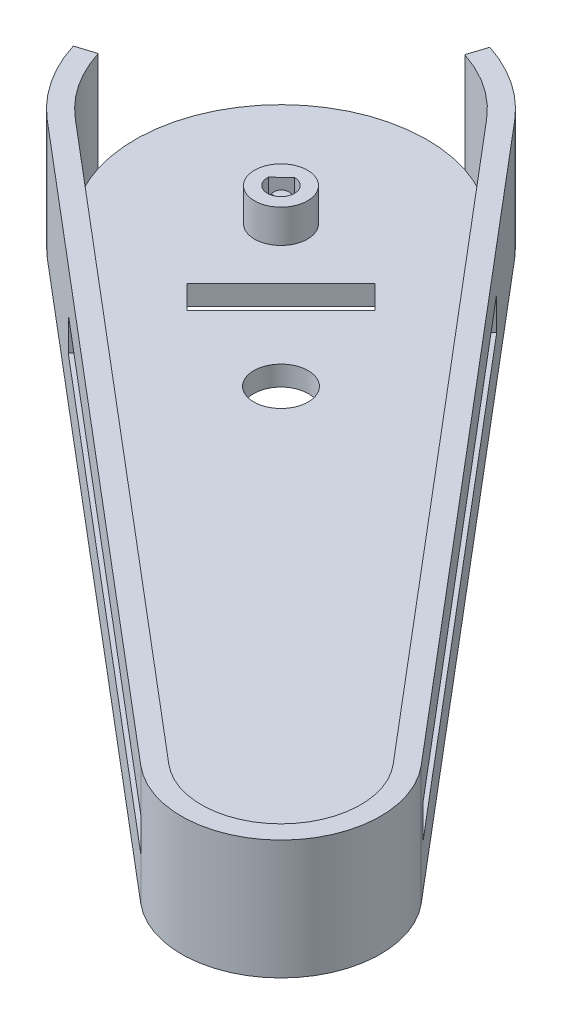
SolidWorks part; units mm, degrees
ref_plane "前视基准面" through (0, 0, 0) normal (0, 0, 1) x (1, 0, 0)
ref_plane "上视基准面" through (0, 0, 0) normal (0, 1, 0) x (1, 0, 0)
ref_plane "右视基准面" through (0, 0, 0) normal (1, 0, 0) x (0, 0, -1)
other "Configuration Table"
sketch "草图2" plane through (0, 0, 0) normal (0, 1, 0) x (1, 0, 0)
  line L0 (-140.5033, 0) -> (6884.6605, 0) construction
  line L1 (0, -140.5033) -> (0, 6884.6605) construction
  line L2 (0, 0) -> (42.4264, -42.4264)
  line L3 (42.4264, -42.4264) -> (-42.4264, 42.4264)
  line L4 (-58.5694, 23.3371) -> (32.7406, -53.88)
  line L5 (-23.3371, 58.5694) -> (53.88, -32.7406)
  circle A0 centre (-42.4264, 42.4264) radius 25
  circle A1 centre (42.4264, -42.4264) radius 15
  dimension "D3" = 50
  dimension "D4" = 30
  dimension "D1" = 60
  dimension "D2" = 120
extrude "凸台-拉伸2" add sketch "草图2" along normal blind 3
sketch "草图4" plane through (0, 3, 0) normal (0, 1, 0) x (1, 0, 0)
  line L0 (-58.5694, 23.3371) -> (32.7406, -53.88)
  line L1 (-58.5694, 23.3371) -> (32.7406, -53.88) construction
  line L2 (-23.3371, 58.5694) -> (53.88, -32.7406)
  line L3 (-23.3371, 58.5694) -> (53.88, -32.7406) construction
  line L4 (-56.6323, 25.6278) -> (34.6777, -51.5893)
  line L5 (-25.6278, 56.6323) -> (51.5893, -34.6777)
  circle A0 centre (-42.4264, 42.4264) radius 25
  circle A1 centre (42.4264, -42.4264) radius 15
  circle A2 centre (-42.4264, 42.4264) radius 22
  circle A3 centre (42.4264, -42.4264) radius 12
  circle A4 centre (-42.4264, 42.4264) radius 2.25
  circle A5 centre (42.4264, -42.4264) radius 2.5
  dimension "D3" = 4.5
  dimension "D4" = 5
  dimension "D1" = 3
  dimension "D2" = 3
extrude "切除-拉伸2" cut sketch "草图4" against normal through all contours A4 | A5
sketch "草图6" plane through (0, 3, 0) normal (0, 1, 0) x (1, 0, 0)
  circle A0 centre (-42.4264, 42.4264) radius 3.5
  dimension "D1" = 7
extrude "切除-拉伸3" cut sketch "草图6" against normal through all
sketch "草图7" plane through (0, 3, 0) normal (0, 1, 0) x (1, 0, 0)
  circle A0 centre (42.4264, -42.4264) radius 3.5
  dimension "D1" = 7
extrude "切除-拉伸4" cut sketch "草图7" against normal through all
sketch "草图8" plane through (0, 3, 0) normal (0, 1, 0) x (1, 0, 0)
  line L0 (-11.8521, 30.3069) -> (-26.8914, 12.9805)
  line L1 (-26.8914, 12.9805) -> (25.2188, -32.2512)
  line L2 (25.2188, -32.2512) -> (33.6267, -22.5647)
  line L3 (33.6267, -22.5647) -> (-15.703, 25.8704)
extrude "切除-拉伸5" cut sketch "草图8" against normal through all contours L2 L3 L0 L1
sketch "草图9" plane through (0, 3, 0) normal (0, 1, 0) x (1, 0, 0)
  line L0 (-23.3371, 58.5694) -> (53.88, -32.7406)
  line L1 (-58.5694, 23.3371) -> (32.7406, -53.88)
  line L2 (-56.6323, 25.6278) -> (34.6777, -51.5893)
  line L3 (-25.6278, 56.6323) -> (51.5893, -34.6777)
  circle A0 centre (-42.4264, 42.4264) radius 25
  circle A1 centre (42.4264, -42.4264) radius 15
  circle A2 centre (-42.4264, 42.4264) radius 22
  circle A3 centre (42.4264, -42.4264) radius 12
  line M8 (-58.5694, 23.3371) -> (32.7406, -53.88)
  arc M9 (32.7406, -53.88) -> (53.88, -32.7406) centre (42.4264, -42.4264) ccw
  line M10 (53.88, -32.7406) -> (-23.3371, 58.5694)
  arc M11 (-23.3371, 58.5694) -> (-58.5694, 23.3371) centre (-42.4264, 42.4264) ccw
  dimension "D1" = 3
  dimension "D2" = 3
extrude "凸台-拉伸4" add sketch "草图9" along normal blind 15 contours A2 L3 A0 L2 M11 | A1 A0 L3 M10 | A1 L2 A0 M8 | A3 L2 A1 L3 M9
sketch "草图10" plane through (0, 3, 0) normal (0, 1, 0) x (1, 0, 0)
  line L0 (-42.4264, 42.4264) -> (42.4264, -42.4264)
  line L1 (42.4264, -42.4264) -> (10.5288, -10.5288)
  line L2 (-26.8914, 12.9805) -> (-15.703, 25.8704)
  line L3 (-15.703, 25.8704) -> (33.6267, -22.5647)
  line L4 (33.6267, -22.5647) -> (25.2188, -32.2512)
  line L5 (25.2188, -32.2512) -> (-26.8914, 12.9805)
  line M5 (33.6267, -22.5647) -> (25.2188, -32.2512)
  line M6 (25.2188, -32.2512) -> (-26.8914, 12.9805)
  line M7 (-26.8914, 12.9805) -> (-15.703, 25.8704)
  line M8 (-15.703, 25.8704) -> (33.6267, -22.5647)
extrude "凸台-拉伸5" add sketch "草图10" against normal blind 3 contours L0 M7 M6 M5 | L0 M7 M5 M8
sketch "草图11" plane through (0, 3, 0) normal (0, 1, 0) x (1, 0, 0)
  line L0 (-42.4264, 42.4264) -> (42.4264, -42.4264)
  line L1 (42.4264, -42.4264) -> (-21.2132, 21.2132)
  circle A0 centre (-21.2132, 21.2132) radius 4.1
  circle A2 centre (42.4264, -42.4264) radius 4.1
  dimension "D3" = 8.2
  dimension "D4" = 8.2
  dimension "D1" = 120
  dimension "D2" = 90
extrude "切除-拉伸6" cut sketch "草图11" against normal blind 3
sketch "草图13" plane through (0, 3, 0) normal (0, 1, 0) x (1, 0, 0)
  circle A0 centre (-42.4264, 42.4264) radius 3.5
extrude "凸台-拉伸6" add sketch "草图13" against normal blind 3
sketch "草图14" plane through (0, 3, 0) normal (0, 1, 0) x (1, 0, 0)
  line L0 (-21.2132, 21.2132) -> (42.4264, -42.4264)
  line L1 (42.4264, -42.4264) -> (-42.4264, 42.4264)
  circle A0 centre (-42.4264, 42.4264) radius 2.05
  dimension "D2" = 4.1
  dimension "D1" = 120
extrude "凸台-拉伸7" add sketch "草图14" along normal blind 5
sketch "草图15" plane through (0, 8, 0) normal (0, 1, 0) x (1, 0, 0)
  circle A0 centre (-42.4264, 42.4264) radius 2.05
  circle A1 centre (-42.4264, 42.4264) radius 4
  dimension "D1" = 8
extrude "凸台-拉伸8" add sketch "草图15" against normal blind 5
sketch "草图17" plane through (0, 8, 0) normal (0, 1, 0) x (1, 0, 0)
  line L0 (-42.4264, 42.4264) -> (-59.3129, 60.8613)
  line L1 (-42.4264, 42.4264) -> (-43.4396, 43.5325)
  line L2 (-43.4396, 43.5325) -> (-40.1632, 46.5337)
  line L3 (-40.1632, 46.5337) -> (-45.1622, 41.9546)
  circle A0 centre (-42.4264, 42.4264) radius 2.05
  arc A1 (-23.3371, 58.5694) -> (-58.5694, 23.3371) centre (-42.4264, 42.4264) ccw construction
  dimension "D1" = 4.1
  dimension "D2" = 1.5
extrude "切除-拉伸7" cut sketch "草图17" against normal through all
sketch "草图18" plane through (-41.5018, 0, -45.3075) normal (0.6755, 0, 0.7374) x (0.7374, 0, -0.6755)
  line L0 (-1.2305, 0) -> (-4.0252, 0)
  line L1 (-2.6278, 0) -> (-2.6278, 4.9532)
  circle A0 centre (-2.6278, 4.9532) radius 1.3973
extrude "切除-拉伸8" cut sketch "草图18" against normal through all contours A0
sketch "草图19" plane through (0, 3, 0) normal (0, 1, 0) x (1, 0, 0)
  line L0 (-42.4264, 42.4264) -> (-66.2933, 34.9851)
  line L1 (-66.2933, 34.9851) -> (-34.7351, 66.2139)
  line L2 (-34.7351, 66.2139) -> (-42.4264, 42.4264)
  circle A0 centre (-42.4264, 42.4264) radius 22
  circle A1 centre (-42.4264, 42.4264) radius 25
extrude "切除-拉伸9" cut sketch "草图19" against normal through all both and the other way through all
sketch "草图20" plane through (-12.9144, 0, 15.2715) normal (-0.6457, 0, 0.7636) x (0.7636, 0, 0.6457)
  line L0 (-32.9451, 18) -> (-32.9451, 0)
  line L1 (-59.7913, 18) -> (59.7913, 18) construction
  line L2 (-59.7913, 0) -> (59.7913, 0) construction
  line L3 (-32.9451, 0) -> (59.7913, 0)
  line L4 (59.7913, 0) -> (59.7913, 18)
  line L5 (59.7913, 18) -> (-32.9451, 18)
  line L6 (-32.9451, 9) -> (59.7913, 9)
  line L7 (-32.9451, 6.5) -> (59.7913, 6.5)
  line L8 (-32.9451, 11.6) -> (59.7913, 11.6)
  dimension "D1" = 2.5
  dimension "D2" = 2.6
extrude "切除-拉伸11" cut sketch "草图20" against normal through all both and the other way through all contours L8 L0 L6 L4 | L0 L7 L4 L6
sketch "草图21" plane through (0, 0, 0) normal (0, -1, 0) x (1, 0, 0)
  line L0 (-21.2132, -21.2132) -> (42.4264, 42.4264)
  line L1 (42.4264, 42.4264) -> (-10.3418, -10.3418)
sketch "草图23" plane through (0, 3, 0) normal (0, 1, 0) x (1, 0, 0)
  line L0 (-21.2132, 21.2132) -> (-42.4264, 42.4264)
  line L1 (-42.4264, 42.4264) -> (-34.6482, 34.6482)
  line L2 (-34.6482, 34.6482) -> (-41.7193, 27.5772)
  line L3 (-41.7193, 27.5772) -> (-27.5772, 41.7193)
  line L4 (-27.5772, 41.7193) -> (-24.0416, 38.1838)
  line L5 (-24.0416, 38.1838) -> (-38.1923, 24.0331)
  line L6 (-38.1923, 24.0331) -> (-41.7193, 27.5772)
  dimension "D1" = 19
  dimension "D2" = 20
  dimension "D3" = 10
  dimension "D4" = 5
extrude "切除-拉伸12" cut sketch "草图23" against normal blind 5 contours L5 L4 L3 L0 | L6 L5 L0 L2
